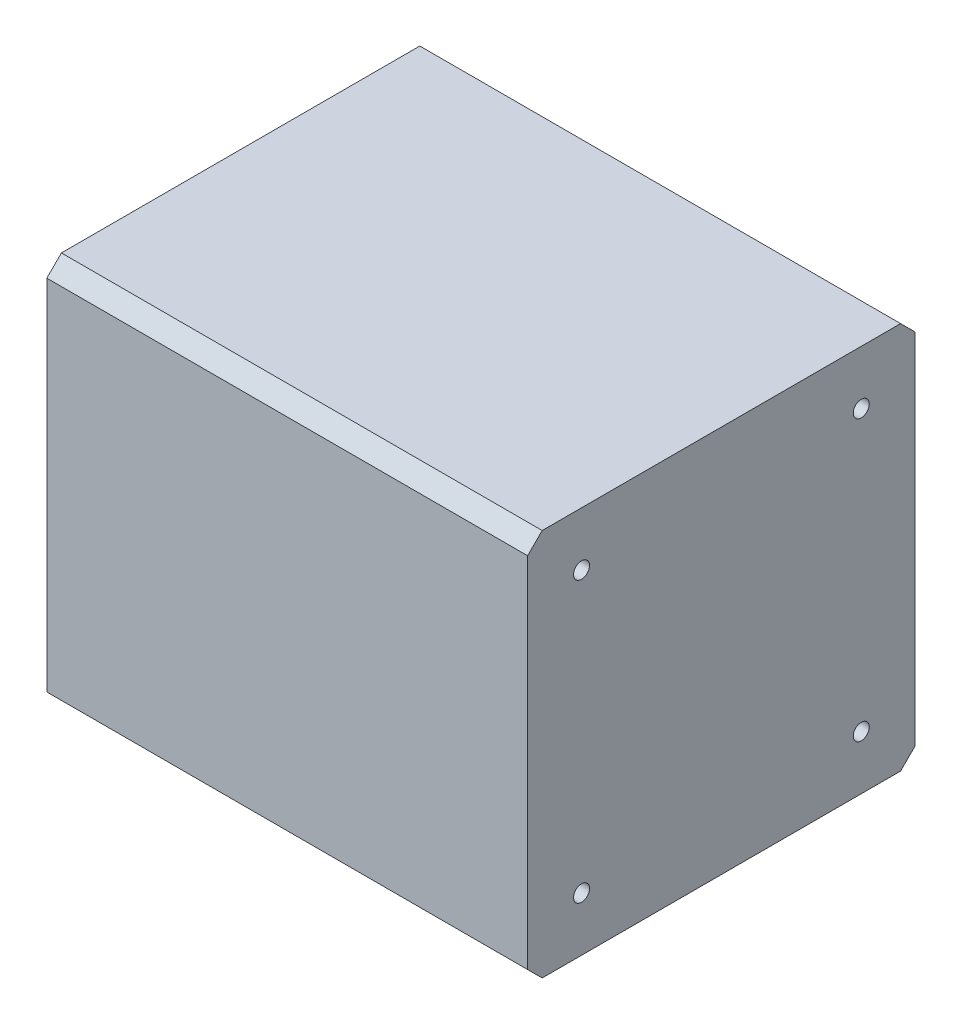
SolidWorks part; units mm, degrees
ref_plane "前视基准面" through (0, 0, 0) normal (0, 0, 1) x (1, 0, 0)
ref_plane "上视基准面" through (0, 0, 0) normal (0, 1, 0) x (1, 0, 0)
ref_plane "右视基准面" through (0, 0, 0) normal (1, 0, 0) x (0, 0, -1)
sketch "草图1" plane through (0, 0, 0) normal (1, 0, 0) x (0, 0, -1)
  line L1 (-66.5, 66.5) -> (66.5, 66.5)
  line L2 (-66.5, 66.5) -> (-66.5, -66.5)
  line L3 (-66.5, -66.5) -> (66.5, -66.5)
  line L4 (66.5, 66.5) -> (66.5, -66.5)
  line L5 (-61.25, 61.25) -> (61.25, 61.25)
  line L6 (-61.25, 61.25) -> (-61.25, -61.25)
  line L7 (-61.25, -61.25) -> (61.25, -61.25)
  line L8 (61.25, 61.25) -> (61.25, -61.25)
  dimension "D1" = 133
  dimension "D2" = 66.5
  dimension "D3" = 66.5
  dimension "D4" = 122.5
  dimension "D5" = 61.25
  dimension "D6" = 61.25
extrude "凸台-拉伸1" add sketch "草图1" along normal blind 160
sketch "草图2" plane through (160, 0, 0) normal (1, 0, 0) x (0, 0, -1)
  line L0 (66.5, 66.5) -> (-66.5, 66.5) construction
  line L1 (66.5, 66.5) -> (-66.5, 66.5)
  line L2 (66.5, -66.5) -> (66.5, 66.5) construction
  line L3 (-66.5, -66.5) -> (66.5, -66.5) construction
  line L4 (-66.5, 66.5) -> (-66.5, -66.5) construction
  line L5 (66.5, -66.5) -> (66.5, 66.5)
  line L6 (-66.5, -66.5) -> (66.5, -66.5)
  line L7 (-66.5, 66.5) -> (-66.5, -66.5)
extrude "凸台-拉伸2" add sketch "草图2" along normal blind 5
chamfer "倒角1" distance 5 angle 45 4 edges at (82.5, -66.5, -66.5) (82.5, -66.5, 66.5) (82.5, 66.5, -66.5) (82.5, 66.5, 66.5)
sketch "草图3" plane through (165, 0, 0) normal (1, 0, 0) x (0, 0, -1)
  line L1 (-48, 48) -> (48, 48) construction
  line L2 (-48, 48) -> (-48, -48) construction
  line L3 (-48, -48) -> (48, -48) construction
  line L4 (48, 48) -> (48, -48) construction
  circle A0 centre (48, 48) radius 2.75
  circle A1 centre (48, -48) radius 2.75
  circle A2 centre (-48, -48) radius 2.75
  circle A3 centre (-48, 48) radius 2.75
  dimension "D4" = 5.5
  dimension "D1" = 96
  dimension "D2" = 48
  dimension "D3" = 48
extrude "切除-拉伸1" cut sketch "草图3" against normal blind 5
sketch "草图4" plane through (0, -66.5, 0) normal (0, -1, 0) x (1, 0, 0)
  line L0 (0, 61.5) -> (0, -61.5) construction
  line L1 (40, 20) -> (0, 20)
  line L3 (40, -20) -> (0, -20)
  line L4 (0, 20) -> (0, -20)
  arc A0 (40, -20) -> (40, 20) centre (40, 0) ccw
  point P8 (0, 0)
  dimension "D1" = 40
  dimension "D2" = 40
extrude "切除-拉伸2" cut sketch "草图4" against normal blind 10
